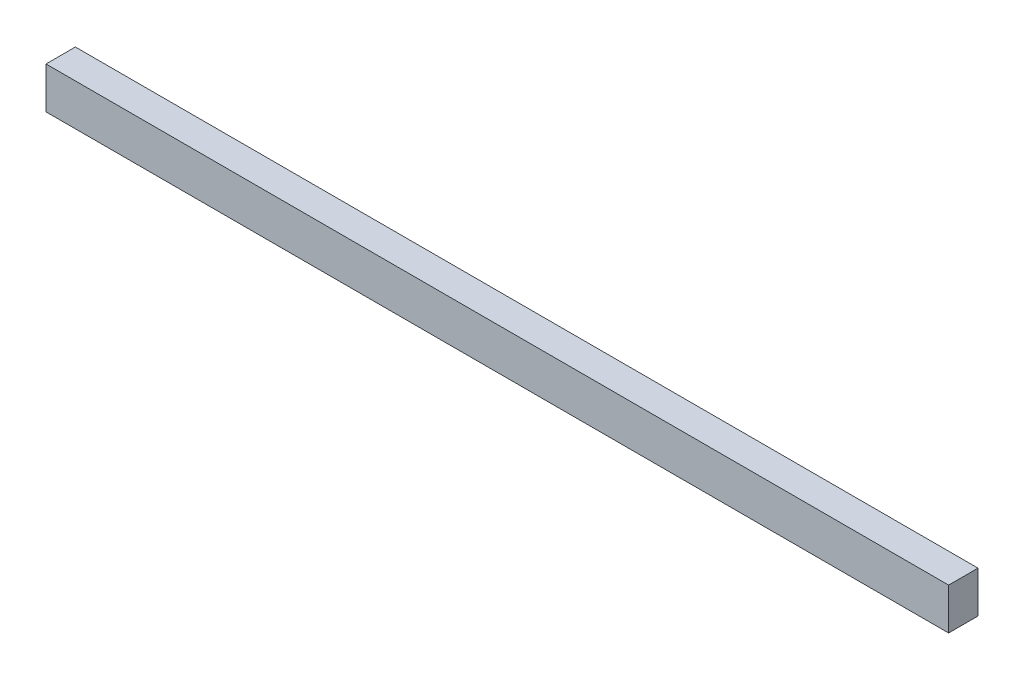
SolidWorks part; units mm, degrees
ref_plane "Front Plane" through (0, 0, 0) normal (0, 0, 1) x (1, 0, 0)
ref_plane "Top Plane" through (0, 0, 0) normal (0, 1, 0) x (1, 0, 0)
ref_plane "Right Plane" through (0, 0, 0) normal (1, 0, 0) x (0, 0, -1)
sketch "Sketch1" plane through (0, 0, 0) normal (0, 0, 1) x (1, 0, 0)
  line L1 (276.225, 12.7) -> (-276.225, 12.7)
  line L2 (276.225, 12.7) -> (276.225, -12.7)
  line L3 (276.225, -12.7) -> (-276.225, -12.7)
  line L4 (-276.225, 12.7) -> (-276.225, -12.7)
  line L5 (276.225, 12.7) -> (-276.225, -12.7) construction
  line L6 (276.225, -12.7) -> (-276.225, 12.7) construction
  point P0 (0, 0)
  dimension "D1" = 25.4
  dimension "D2" = 552.45
extrude "Boss-Extrude1" add sketch "Sketch1" along normal blind 17.9832
